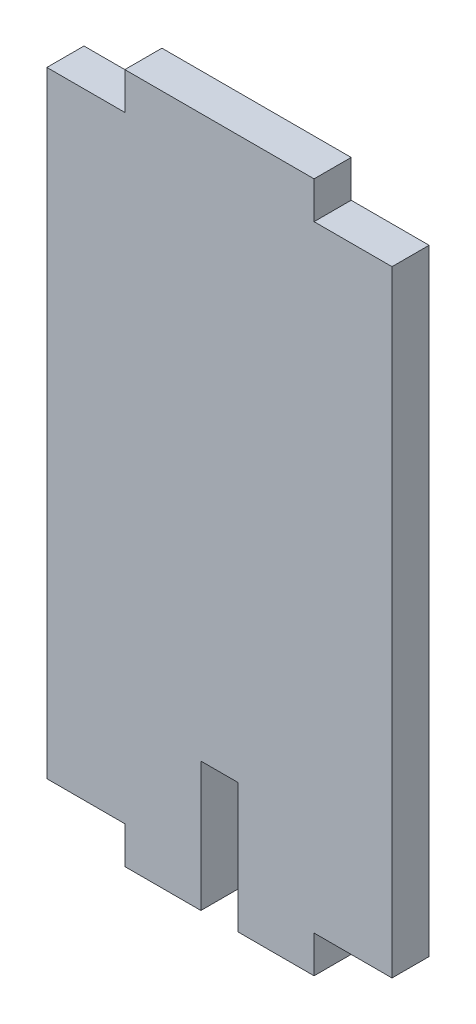
SolidWorks part; units mm, degrees
ref_plane "Front Plane" through (0, 0, 0) normal (0, 0, 1) x (1, 0, 0)
ref_plane "Top Plane" through (0, 0, 0) normal (0, 1, 0) x (1, 0, 0)
ref_plane "Right Plane" through (0, 0, 0) normal (1, 0, 0) x (0, 0, -1)
sketch "Sketch1" plane through (0, 0, 0) normal (0, 0, 1) x (1, 0, 0)
  line L1 (0, 0) -> (50.8, 0)
  line L2 (0, 0) -> (0, 101.6)
  line L3 (0, 101.6) -> (50.8, 101.6)
  line L4 (50.8, 0) -> (50.8, 101.6)
  line L5 (25.4, 101.6) -> (25.4, 0) construction
  line L6 (0, 50.8) -> (50.8, 50.8) construction
  point P120 (25.4, 50.8)
  dimension "D1" = 50.8
  dimension "D2" = 101.6
extrude "Boss-Extrude1" add sketch "Sketch1" along normal blind 5.461
sketch "Sketch2" plane through (0, 0, 5.461) normal (0, 0, 1) x (1, 0, 0)
  line L0 (25.4, 101.6) -> (25.4, 0) construction
  line L1 (50.8, 101.6) -> (0, 101.6) construction
  line L2 (0, 0) -> (50.8, 0) construction
  line L3 (50.8, 98.8695) -> (39.3277, 98.8695) construction
  line L4 (22.6695, 0) -> (28.1305, 0)
  line L5 (22.6695, 0) -> (22.6695, 19.05)
  line L6 (22.6695, 19.05) -> (28.1305, 19.05)
  line L7 (28.1305, 0) -> (28.1305, 19.05)
  line L8 (25.4, 19.05) -> (25.4, 0) construction
  line L9 (22.6695, 9.525) -> (28.1305, 9.525) construction
  line L10 (0, 101.6) -> (11.4723, 101.6)
  line L11 (0, 101.6) -> (0, 96.139)
  line L12 (0, 96.139) -> (11.4723, 96.139)
  line L13 (11.4723, 101.6) -> (11.4723, 96.139)
  line L14 (5.7362, 96.139) -> (5.7362, 101.6) construction
  line L15 (0, 98.8695) -> (11.4723, 98.8695) construction
  line L16 (45.0638, 96.139) -> (45.0638, 101.6) construction
  line L17 (39.3277, 101.6) -> (39.3277, 96.139)
  line L18 (50.8, 96.139) -> (39.3277, 96.139)
  line L19 (50.8, 101.6) -> (50.8, 96.139)
  line L20 (50.8, 101.6) -> (39.3277, 101.6)
  line L21 (0, 50.8) -> (50.8, 50.8) construction
  line L22 (0, 101.6) -> (0, 0) construction
  line L23 (50.8, 0) -> (50.8, 101.6) construction
  line L24 (45.0638, 5.461) -> (45.0638, 0) construction
  line L25 (50.8, 2.7305) -> (39.3277, 2.7305) construction
  line L26 (50.8, 0) -> (39.3277, 0)
  line L27 (50.8, 0) -> (50.8, 5.461)
  line L28 (50.8, 5.461) -> (39.3277, 5.461)
  line L29 (39.3277, 0) -> (39.3277, 5.461)
  line L30 (0, 2.7305) -> (11.4723, 2.7305) construction
  line L31 (5.7362, 5.461) -> (5.7362, 0) construction
  line L32 (11.4723, 0) -> (11.4723, 5.461)
  line L33 (0, 5.461) -> (11.4723, 5.461)
  line L34 (0, 0) -> (0, 5.461)
  line L35 (0, 0) -> (11.4723, 0)
  point P22 (45.0638, 98.8695)
  point P37 (45.0638, 2.7305)
  point P46 (5.7362, 2.7305)
  point P178 (25.4, 9.525)
  point P326 (5.7362, 98.8695)
  dimension "D1" = 19.05
  dimension "D2" = 5.461
  dimension "D3" = 5.461
  dimension "D4" = 11.4723
extrude "Cut-Extrude1" cut sketch "Sketch2" against normal blind 5.461
equation "\"Stock Thickness\"= .215in"
equation "\"D1@Boss-Extrude1\"=\"Stock Thickness\""
equation "\"D2@Sketch2\"=\"Stock Thickness\""
equation "\"D3@Sketch2\"=\"Stock Thickness\""
equation "\"D4@Sketch2\"=(\"D1@Sketch1\"/3)-\"Stock Thickness\""
equation "\"D1@Cut-Extrude1\"=\"Stock Thickness\""
equation "\"Joint Length\"= .75in"
equation "\"D1@Sketch2\"=\"Joint Length\""
